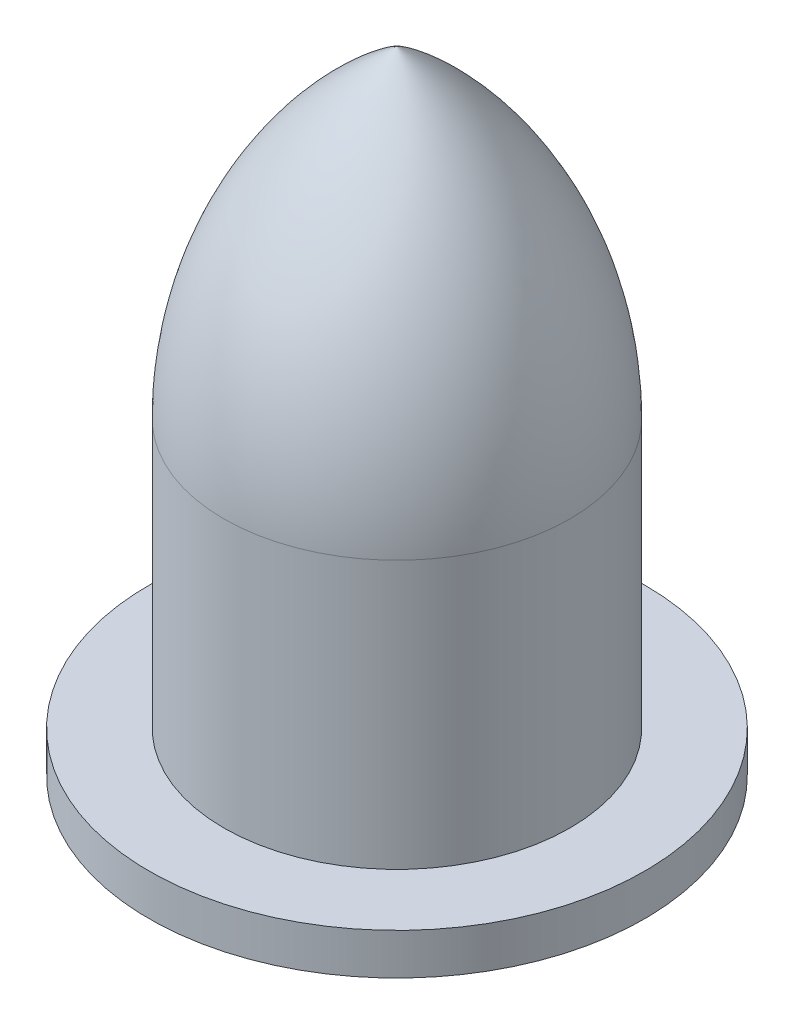
SolidWorks part; units mm, degrees
ref_plane "Front Plane" through (0, 0, 0) normal (0, 0, 1) x (1, 0, 0)
ref_plane "Top Plane" through (0, 0, 0) normal (0, 1, 0) x (1, 0, 0)
ref_plane "Right Plane" through (0, 0, 0) normal (1, 0, 0) x (0, 0, -1)
sketch "Sketch1" plane through (0, 0, 0) normal (0, 0, 1) x (1, 0, 0)
  line L0 (0, 0) -> (0, 42.9203) construction
  line L1 (6, 14.8949) -> (6, 15.8949)
  line L2 (6, 15.8949) -> (4.1912, 15.8949)
  line L3 (4.1912, 15.8949) -> (4.1912, 22.3776)
  line L4 (6, 0) -> (6, 42.9203) construction
  line L5 (6, 14.8949) -> (2.5, 14.8949)
  line L6 (2.5, 14.8949) -> (2.5, 22.1647)
  line L7 (2.5, 22.1647) -> (0, 23.9732)
  line L8 (0, 30.1949) -> (0, 23.9732)
  arc A0 (4.1912, 22.3776) -> (0, 30.1949) centre (-5.1946, 22.3776) ccw
  dimension "D6" = 9.3859
  dimension "D2" = 2.5
  dimension "D3" = 1
  dimension "D4" = 15.3
  dimension "D5" = 7.2698
  dimension "D7" = 4.1912
  dimension "D8" = 9.0783
  dimension "D1" = 6
revolve "Revolve1" add sketch "Sketch1" angle 360 about L0
